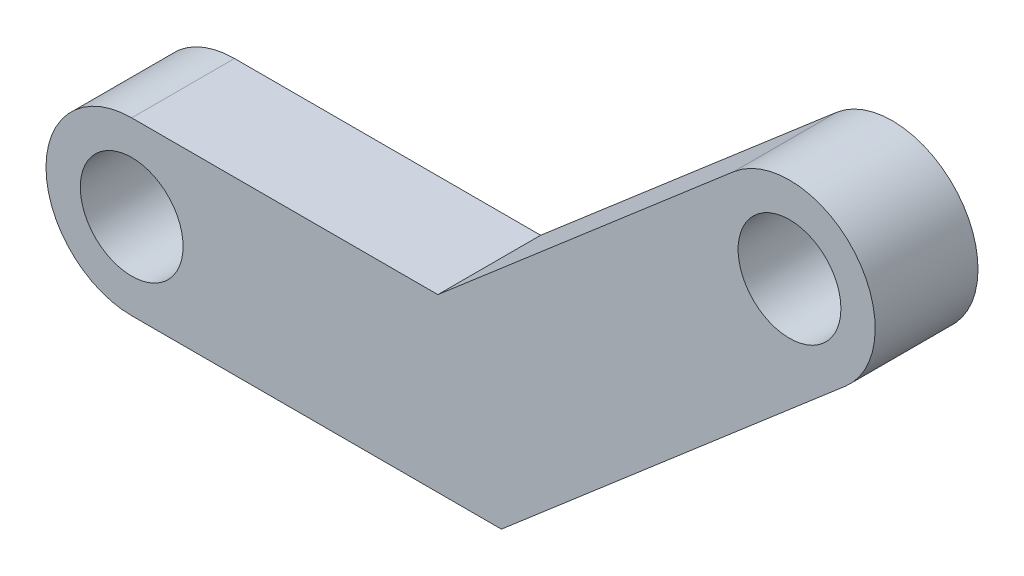
SolidWorks part; units mm, degrees
ref_plane "Front Plane" through (0, 0, 0) normal (0, 0, 1) x (1, 0, 0)
ref_plane "Top Plane" through (0, 0, 0) normal (0, 1, 0) x (1, 0, 0)
ref_plane "Right Plane" through (0, 0, 0) normal (1, 0, 0) x (0, 0, -1)
sketch "Sketch1" plane through (0, 0, 0) normal (0, 0, 1) x (1, 0, 0)
  line L0 (3.8777, 0) -> (13.7377, 0) construction
  line L1 (13.7377, 0) -> (23.0718, 8.0257) construction
  line L2 (3.8777, -2.5) -> (14.6648, -2.5)
  line L3 (14.6648, -2.5) -> (24.7017, 6.1301)
  line L4 (3.8777, 2.5) -> (12.8107, 2.5)
  line L5 (12.8107, 2.5) -> (21.4419, 9.9213)
  arc A0 (3.8777, -2.5) -> (3.8777, 2.5) centre (3.8777, 0) cw
  arc A1 (24.7017, 6.1301) -> (21.4419, 9.9213) centre (23.0718, 8.0257) ccw
  circle A2 centre (23.0718, 8.0257) radius 1.5
  circle A3 centre (3.8777, 0) radius 1.5
  dimension "D6" = 3
  dimension "D7" = 3
  dimension "D1" = 9.86
  dimension "D2" = 12.31
  dimension "D3" = 139.31
  dimension "D4" = 2.5
  dimension "D5" = 2.5
extrude "Boss-Extrude1" add sketch "Sketch1" along normal blind 3
